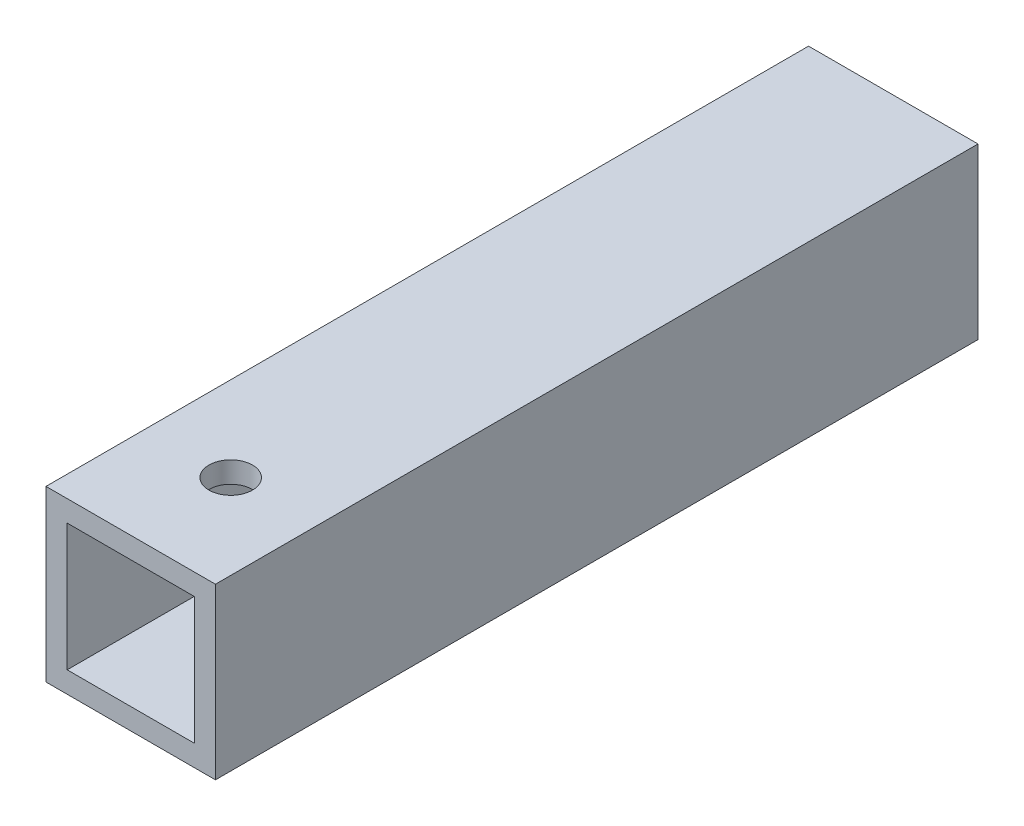
SolidWorks part; units mm, degrees
ref_plane "Front Plane" through (0, 0, 0) normal (0, 0, 1) x (1, 0, 0)
ref_plane "Top Plane" through (0, 0, 0) normal (0, 1, 0) x (1, 0, 0)
ref_plane "Right Plane" through (0, 0, 0) normal (1, 0, 0) x (0, 0, -1)
sketch "Sketch1" plane through (0, 0, 0) normal (0, 0, 1) x (1, 0, 0)
  line L1 (12.7, -12.7) -> (-12.7, -12.7)
  line L2 (12.7, -12.7) -> (12.7, 12.7)
  line L3 (12.7, 12.7) -> (-12.7, 12.7)
  line L4 (-12.7, -12.7) -> (-12.7, 12.7)
  line L5 (12.7, -12.7) -> (-12.7, 12.7) construction
  line L6 (12.7, 12.7) -> (-12.7, -12.7) construction
  point P1 (0, 0)
extrude "Boss-Extrude1" add sketch "Sketch1" along normal blind 114.3
sketch "Sketch2" plane through (0, 0, 0) normal (0, 0, 1) x (1, 0, 0)
  line L0 (-12.7, 12.7) -> (-12.7, -12.7) construction
  line L1 (9.525, -9.525) -> (-9.525, -9.525)
  line L2 (9.525, -9.525) -> (9.525, 9.525)
  line L3 (9.525, 9.525) -> (-9.525, 9.525)
  line L4 (-9.525, -9.525) -> (-9.525, 9.525)
  line L5 (9.525, -9.525) -> (-9.525, 9.525) construction
  line L6 (9.525, 9.525) -> (-9.525, -9.525) construction
  line L7 (12.7, 12.7) -> (-12.7, 12.7) construction
  point P0 (0, 0)
  dimension "D1" = 3.175
  dimension "D2" = 3.175
extrude "Cut-Extrude1" cut sketch "Sketch2" along normal through all
sketch "Sketch3" plane through (0, 12.7, 0) normal (0, 1, 0) x (1, 0, 0)
  line L0 (12.7, -114.3) -> (-12.7, -114.3) construction
  line L2 (-12.7, -114.3) -> (-12.7, 0) construction
  circle A0 centre (0, -99.314) radius 3.2639
  dimension "D1" = 6.5278
  dimension "D2" = 14.986
  dimension "D3" = 12.7
extrude "Cut-Extrude2" cut sketch "Sketch3" against normal through all
